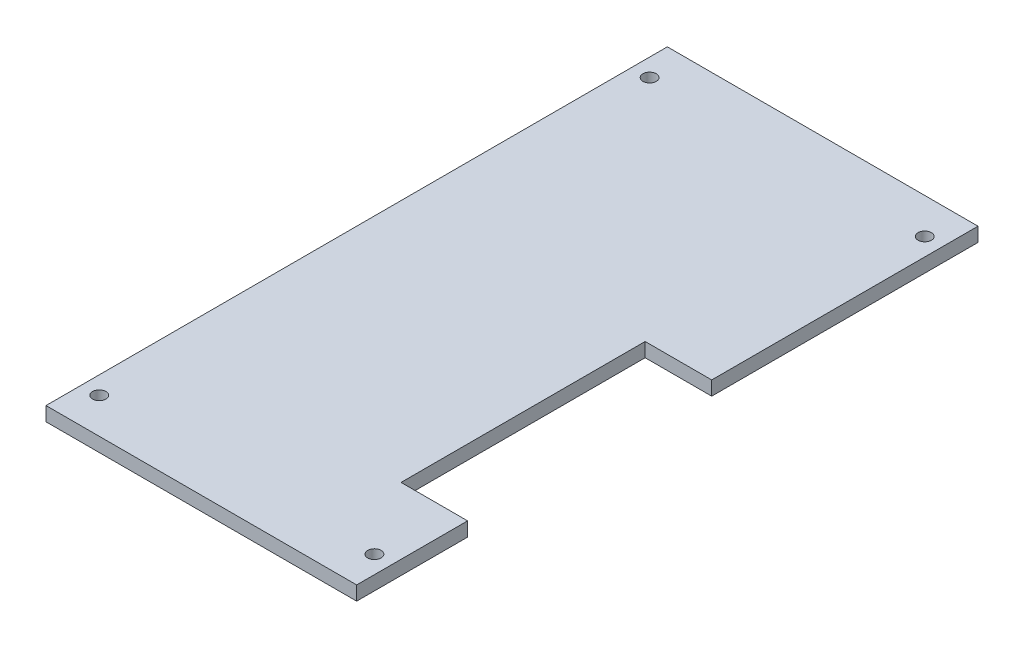
SolidWorks part; units mm, degrees
ref_plane "Front Plane" through (0, 0, 0) normal (0, 0, 1) x (1, 0, 0)
ref_plane "Top Plane" through (0, 0, 0) normal (0, 1, 0) x (1, 0, 0)
ref_plane "Right Plane" through (0, 0, 0) normal (1, 0, 0) x (0, 0, -1)
sketch "Sketch1" plane through (0, 0, 0) normal (0, 1, 0) x (1, 0, 0)
  line L0 (35, 10) -> (20, 10)
  line L1 (35, -70) -> (-35, -70)
  line L2 (35, -70) -> (35, -45)
  line L3 (35, 70) -> (-35, 70)
  line L4 (-35, -70) -> (-35, 70)
  line L5 (35, -70) -> (-35, 70) construction
  line L6 (35, 70) -> (-35, -70) construction
  line L7 (20, 10) -> (20, -45)
  line L8 (20, -45) -> (35, -45)
  line L9 (0, -70) -> (0, 70) construction
  line L10 (-35, 0) -> (35, 0) construction
  line L11 (35, 10) -> (35, 70)
  circle A0 centre (31, -62) radius 1.5
  circle A1 centre (-31, -62) radius 1.5
  circle A2 centre (-31, 62) radius 1.5
  circle A3 centre (31, 62) radius 1.5
  point P0 (0, 0)
  dimension "D6" = 4
  dimension "D1" = 70
  dimension "D2" = 140
  dimension "D3" = 15
  dimension "D4" = 55
  dimension "D5" = 25
  dimension "D7" = 8
extrude "Boss-Extrude1" add sketch "Sketch1" along normal blind 3.175
